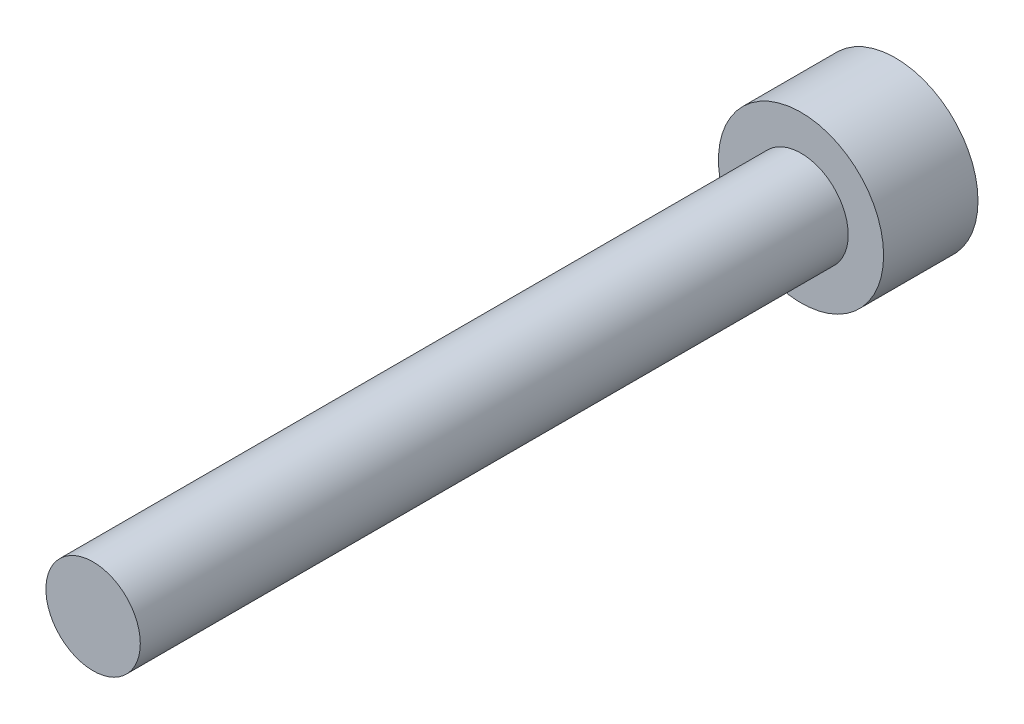
SolidWorks part; units mm, degrees
ref_plane "Спереди" through (0, 0, 0) normal (0, 0, 1) x (1, 0, 0)
ref_plane "Сверху" through (0, 0, 0) normal (0, 1, 0) x (1, 0, 0)
ref_plane "Справа" through (0, 0, 0) normal (1, 0, 0) x (0, 0, -1)
sketch "Эскиз1" plane through (0, 0, 0) normal (0, 0, 1) x (1, 0, 0)
  circle A0 centre (0, 0) radius 3.5
  point P2 (0, 0)
  point P4 (0, 0)
  dimension "D1" = 7
extrude "Шляпка" add sketch "Эскиз1" along normal blind 4
sketch "Эскиз2" plane through (0, 0, 4) normal (0, 0, 1) x (1, 0, 0)
  circle A0 centre (0, 0) radius 2
  dimension "D1" = 4
extrude "Бобышка-Вытянуть2" add sketch "Эскиз2" along normal blind 30
